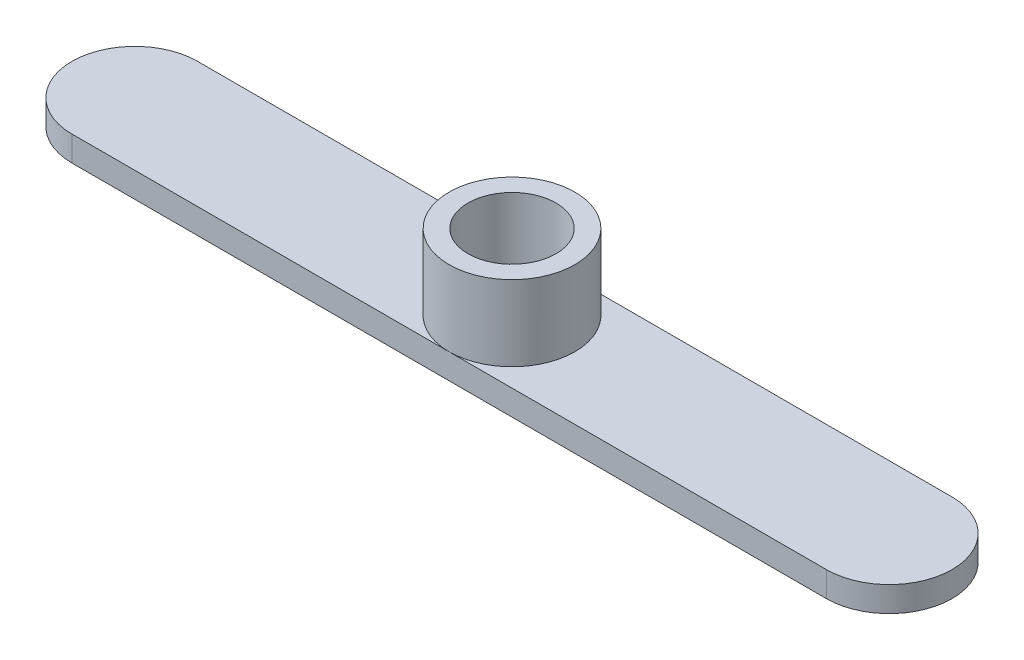
SolidWorks part; units mm, degrees
ref_plane "前视基准面" through (0, 0, 0) normal (0, 0, 1) x (1, 0, 0)
ref_plane "上视基准面" through (0, 0, 0) normal (0, 1, 0) x (1, 0, 0)
ref_plane "右视基准面" through (0, 0, 0) normal (1, 0, 0) x (0, 0, -1)
other "Configuration Table"
sketch "草图1" plane through (0, 0, 0) normal (0, 1, 0) x (1, 0, 0)
  line L1 (-15, 2.5) -> (15, 2.5)
  line L3 (-15, -2.5) -> (15, -2.5)
  line L5 (-15, 2.5) -> (15, -2.5) construction
  line L6 (-15, -2.5) -> (15, 2.5) construction
  arc A0 (-15, 2.5) -> (-15, -2.5) centre (-15, 0) ccw
  arc A1 (15, -2.5) -> (15, 2.5) centre (15, 0) ccw
  point P0 (0, 0)
  dimension "D3" = 2.5
  dimension "D4" = 2.5
  dimension "D1" = 30
  dimension "D2" = 5
extrude "凸台-拉伸1" add sketch "草图1" along normal blind 1
sketch "草图2" plane through (0, 0, 0) normal (0, 1, 0) x (1, 0, 0)
  circle A0 centre (0, 0) radius 2.5
  circle A1 centre (0, 0) radius 1.75
  dimension "D1" = 5
  dimension "D2" = 3.5
extrude "凸台-拉伸2" add sketch "草图2" along normal blind 4
sketch "草图3" plane through (0, 0, 0) normal (0, 1, 0) x (1, 0, 0)
  circle A0 centre (0, 0) radius 1
  dimension "D1" = 2
extrude "切除-拉伸1" cut sketch "草图3" along normal blind 4
sketch "草图4" plane through (0, 0, 0) normal (0, 1, 0) x (1, 0, 0)
  circle A0 centre (0, 0) radius 1.5
  dimension "D1" = 3
extrude "切除-拉伸2" cut sketch "草图4" along normal blind 0.5
